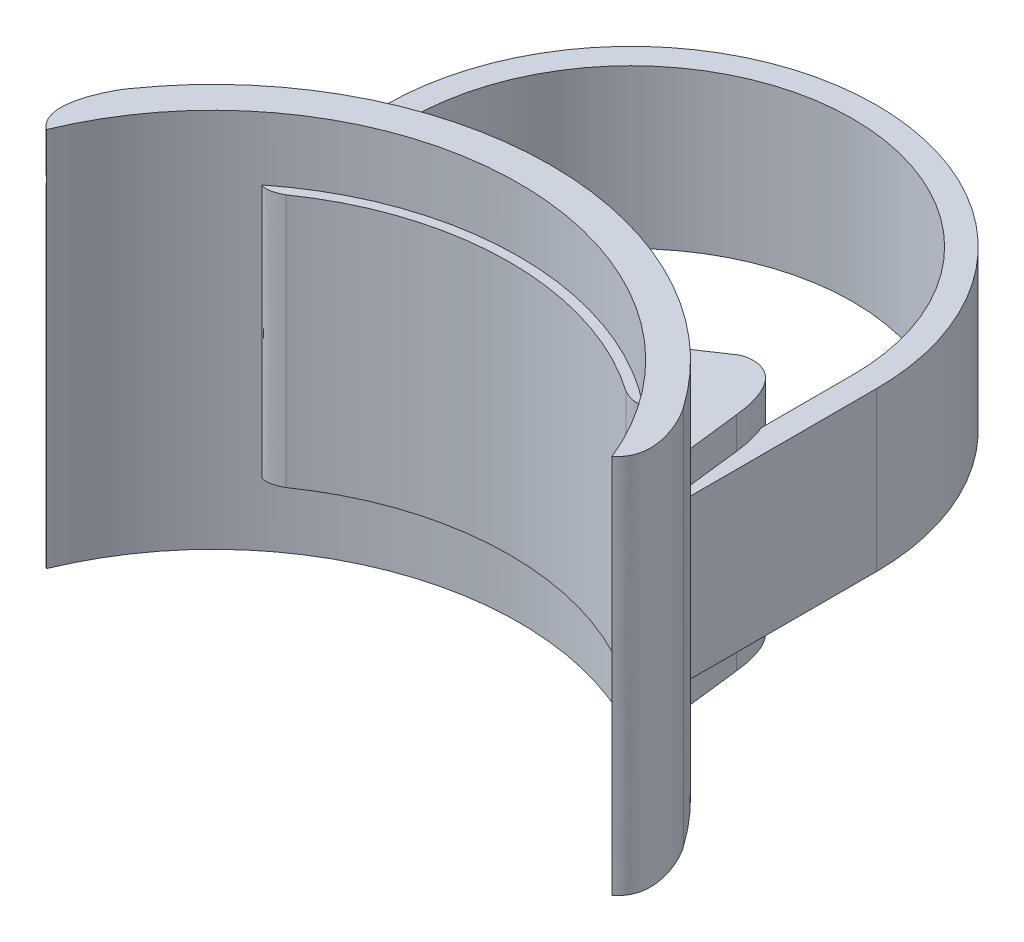
SolidWorks part; units mm, degrees
ref_plane "Front Plane" through (0, 0, 0) normal (0, 0, 1) x (1, 0, 0)
ref_plane "Top Plane" through (0, 0, 0) normal (0, 1, 0) x (1, 0, 0)
ref_plane "Right Plane" through (0, 0, 0) normal (1, 0, 0) x (0, 0, -1)
sketch "Sketch1" plane through (0, 0, 0) normal (0, 1, 0) x (1, 0, 0)
  line L0 (0, 0) -> (0, 18.0815) construction
  arc A0 (8.9279, 3.6627) -> (-8.9279, 3.6627) centre (0, 0) ccw
  arc A1 (8.7249, 6.1072) -> (-8.7249, 6.1072) centre (0, 0) ccw
  circle A2 centre (0, 0) radius 10.65 construction
  circle A3 centre (0, 0) radius 9.65 construction
  spline S0 degree 3 poles (-8.7249, 6.1072) (-8.9049, 5.8939) (-9.8035, 4.3226) (-8.9279, 3.6627) knots 0 0 0 0 1 1 1 1
  spline S1 degree 3 poles (8.7249, 6.1072) (8.9049, 5.8939) (9.8035, 4.3226) (8.9279, 3.6627) knots 0 0 0 0 1 1 1 1
  point P1 (8.9279, 3.6627)
  point P11 (8.7249, 6.1072)
  dimension "D1" = 19.3
  dimension "D2" = 1
extrude "Boss-Extrude1" add sketch "Sketch1" along normal mid plane 12
sketch "Sketch2" plane through (0, 0, 0) normal (0, 1, 0) x (1, 0, 0)
  line L0 (0, 0) -> (0, 16.5425) construction
  line L1 (0, 10.65) -> (0, 9.5079) construction
  line L2 (-7.75, 13.1801) -> (-7.75, 6.9768)
  line L3 (-7.75, 6.9768) -> (-7, 6.9768)
  line L4 (-7, 6.9768) -> (-7, 13.1801)
  line L5 (7.75, 13.1801) -> (7.75, 6.9768)
  line L6 (7.75, 6.9768) -> (7, 6.9768)
  line L7 (7, 6.9768) -> (7, 13.1801)
  arc A0 (7.75, 13.1801) -> (-7.75, 13.1801) centre (0, 13.1801) ccw
  arc A1 (8.7249, 6.1072) -> (-8.7249, 6.1072) centre (0, 0) ccw construction
  arc A2 (7, 13.1801) -> (-7, 13.1801) centre (0, 13.1801) ccw
  circle A3 centre (0, 13.1801) radius 7.75 construction
  circle A4 centre (0, 13.1801) radius 7 construction
  point P10 (0, 9.1801)
  dimension "D1" = 4
  dimension "D4" = 7
  dimension "D2" = 0.75
  dimension "D3" = 0.75
extrude "Boss-Extrude2" add sketch "Sketch2" along normal mid plane 5
sketch "Sketch3" plane through (0, 0, 0) normal (0, 1, 0) x (1, 0, 0)
  line L0 (0, 0) -> (0, 21.428) construction
  line L1 (4.0514, 9.8493) -> (5.6379, 10.9141)
  line L2 (-7.45, 7.6105) -> (-7.2561, 9.255)
  line L3 (-4.0514, 9.8493) -> (-5.6379, 10.9141)
  line L4 (7.45, 7.6105) -> (7.2561, 9.255)
  arc A0 (-4.0514, 9.8493) -> (-7.45, 7.6105) centre (0, 0) ccw
  arc A3 (4.0514, 9.8493) -> (7.45, 7.6105) centre (0, 0) cw
  arc A4 (8.7249, 6.1072) -> (-8.7249, 6.1072) centre (0, 0) ccw construction
  arc A5 (8.7249, 6.1072) -> (0, 10.65) centre (0, 0) ccw
  spline S0 degree 3 poles (-7.2561, 9.255) (-7.0416, 11.2062) (-5.9815, 11.0974) (-5.6379, 10.9141) knots 0 0 0 0 1 1 1 1
  spline S1 degree 3 poles (7.2561, 9.255) (7.0416, 11.2062) (5.9815, 11.0974) (5.6379, 10.9141) knots 0 0 0 0 1 1 1 1
  point P7 (-4.0514, 9.8493)
  point P8 (-5.6379, 10.9141)
  point P15 (-7.2561, 9.255)
extrude "Boss-Extrude3" add sketch "Sketch3" along normal mid plane 7 contours S0 L2 A0 L3 | L4 S1 L1 A3
sketch "Sketch4" plane through (0, 0, 0) normal (0, 1, 0) x (1, 0, 0)
  line L0 (0, 0) -> (0, 18.4265) construction
  arc A0 (8.9279, 3.6627) -> (-8.9279, 3.6627) centre (0, 0) ccw construction
  arc A1 (6.0133, 7.5474) -> (-6.0133, 7.5474) centre (0, 0) ccw
  arc A2 (5.3593, 7.6616) -> (-5.3593, 7.6616) centre (0, 0) ccw
  arc A3 (8.6503, 3.5488) -> (-8.6503, 3.5488) centre (0, 0) ccw construction
  arc A4 (8.9279, 3.6627) -> (-8.9279, 3.6627) centre (0, 0) ccw construction
  spline S0 degree 2 poles (-5.3593, 7.6616) (-5.7833, 7.4377) (-6.0133, 7.5474) knots 0 0 0 1 1 1
  spline S1 degree 2 poles (5.3593, 7.6616) (5.7833, 7.4377) (6.0133, 7.5474) knots 0 0 0 1 1 1
  dimension "D1" = 0.3
extrude "Boss-Extrude4" add sketch "Sketch4" along normal mid plane 8
sketch "Sketch5" plane through (0, 0, 0) normal (0, 1, 0) x (1, 0, 0)
  line L0 (0, 22.7822) -> (0, 0) construction
  point P0 (0, 14.9963)
  point P5 (0, 14.6514)
  point P6 (0, 14.9963)
sketch "Sketch6" plane through (0, 0, 0) normal (1, 0, 0) x (0, 0, -1)
  line L0 (14.9963, -5.2938) -> (14.9963, 5.2938) construction
  point P5 (14.9963, 0)
